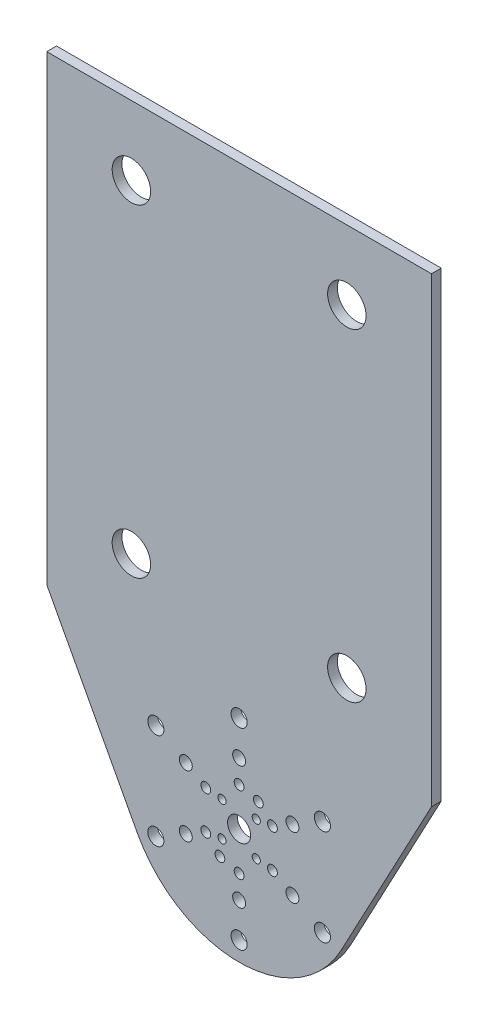
SolidWorks part; units mm, degrees
ref_plane "Front Plane" through (0, 0, 0) normal (0, 0, 1) x (1, 0, 0)
ref_plane "Top Plane" through (0, 0, 0) normal (0, 1, 0) x (1, 0, 0)
ref_plane "Right Plane" through (0, 0, 0) normal (1, 0, 0) x (0, 0, -1)
sketch "Sketch1" plane through (0, 0, 0) normal (0, 0, 1) x (1, 0, 0)
  line L0 (0, 375) -> (0, 0) construction
  line L1 (-125, 375) -> (125, 375)
  line L2 (-125, 375) -> (-125, 75)
  line L3 (-125, 75) -> (125, 75) construction
  line L4 (125, 375) -> (125, 75)
  line L5 (-66.1765, -35.2941) -> (-125, 75)
  line L6 (66.1765, -35.2941) -> (125, 75)
  arc A0 (-66.1765, -35.2941) -> (66.1765, -35.2941) centre (0, 0) ccw
  circle A1 centre (0, 0) radius 75 construction
  dimension "D3" = 75
  dimension "D1" = 250
  dimension "D2" = 300
extrude "Boss-Extrude1" add sketch "Sketch1" along normal blind 6.35
hole_wizard "SIA20 (80mm x M8 x 6)" positions "Sketch3" profile "Sketch2" hole size "M8" standard "ANSI Metric" end condition through all
sketch "Sketch3" plane through (0, 0, 6.35) normal (0, 0, 1) x (1, 0, 0)
  line L0 (0, 40) -> (0, -40) construction
  line L1 (-34.641, -20) -> (34.641, 20) construction
  line L2 (-34.641, 20) -> (34.641, -20) construction
  circle A0 centre (0, 0) radius 40 construction
  point P0 (-34.641, 20)
  point P14 (-34.641, -20)
  point P16 (0, -40)
  point P18 (34.641, -20)
  point P20 (34.641, 20)
  point P22 (0, 40)
  dimension "D1" = 80
  dimension "D2" = 60
  dimension "D3" = 60
sketch "Sketch2" plane through (-34.641, 20, 6.35) normal (1, 0, 0) x (0, -1, 0)
  line L0 (0, 0) -> (0, 6.35)
  line L1 (0, 6.35) -> (4.2, 6.35)
  line L2 (4.2, 6.35) -> (4.2, 0)
  line L5 (4.2, 0) -> (0, 0)
  line L11 (0, -6.35) -> (0, 107.95) construction
  dimension "Thru Hole Dia." = 8.4
  dimension "Thru Hole Depth" = 6.35
hole_wizard "IRB2400 (50mm x M6 x 6)" positions "Sketch7" profile "Sketch6" hole size "M6" standard "ANSI Metric" end condition through all
sketch "Sketch7" plane through (0, 0, 6.35) normal (0, 0, 1) x (1, 0, 0)
  line L0 (-34.641, 20) -> (34.641, -20) construction
  line L1 (-34.641, -20) -> (34.641, 20) construction
  circle A0 centre (0, 0) radius 25 construction
  point P6 (0, 25)
  point P8 (21.6506, -12.5)
  point P10 (21.6506, 12.5)
  point P14 (-21.6506, 12.5)
  point P16 (-21.6506, -12.5)
  point P18 (0, -25)
  dimension "D1" = 50
sketch "Sketch6" plane through (0, 25, 6.35) normal (1, 0, 0) x (0, -1, 0)
  line L0 (0, 0) -> (0, 6.35)
  line L1 (0, 6.35) -> (3.2, 6.35)
  line L2 (3.2, 6.35) -> (3.2, 0)
  line L5 (3.2, 0) -> (0, 0)
  line L11 (0, -6.35) -> (0, 107.95) construction
  dimension "Thru Hole Dia." = 6.4
  dimension "Thru Hole Depth" = 6.35
hole_wizard "UR5 (50mm x M6 x 4)" positions "Sketch9" profile "Sketch8" hole size "M6" standard "ANSI Metric" end condition through all
sketch "Sketch9" plane through (0, 0, 6.35) normal (0, 0, 1) x (1, 0, 0)
  line L0 (0, 40) -> (0, -40) construction
  line L2 (12.5, 21.6506) -> (21.6506, -12.5) construction
  line L3 (12.5, 21.6506) -> (-21.6506, 12.5) construction
  line L4 (-21.6506, 12.5) -> (-12.5, -21.6506) construction
  line L5 (21.6506, -12.5) -> (-12.5, -21.6506) construction
  circle A0 centre (0, 0) radius 25 construction
  point P0 (12.5, 21.6506)
  point P190 (-21.6506, 12.5)
  point P192 (-12.5, -21.6506)
  point P194 (21.6506, -12.5)
  dimension "D1" = 50
  dimension "D2" = 75
sketch "Sketch8" plane through (12.5, 21.6506, 6.35) normal (1, 0, 0) x (0, -1, 0)
  line L0 (0, 0) -> (0, 6.35)
  line L1 (0, 6.35) -> (3.2, 6.35)
  line L2 (3.2, 6.35) -> (3.2, 0)
  line L5 (3.2, 0) -> (0, 0)
  line L11 (0, -6.35) -> (0, 107.95) construction
  dimension "Thru Hole Dia." = 6.4
  dimension "Thru Hole Depth" = 6.35
hole_wizard "R2000 (125mm x M10 x 6)" positions "Sketch11" profile "Sketch10" hole size "M10" standard "ANSI Metric" end condition through all
sketch "Sketch11" plane through (0, 0, 6.35) normal (0, 0, 1) x (1, 0, 0)
  line L0 (-34.641, 20) -> (34.641, -20) construction
  line L3 (-34.641, -20) -> (34.641, 20) construction
  circle A0 centre (0, 0) radius 62.5 construction
  point P0 (-54.1266, 31.25)
  point P6 (0, 62.5)
  point P8 (54.1266, 31.25)
  point P10 (54.1266, -31.25)
  point P12 (0, -62.5)
  point P14 (-54.1266, -31.25)
  dimension "D1" = 125
sketch "Sketch10" plane through (-54.1266, 31.25, 6.35) normal (1, 0, 0) x (0, -1, 0)
  line L0 (0, 0) -> (0, 6.35)
  line L1 (0, 6.35) -> (5.25, 6.35)
  line L2 (5.25, 6.35) -> (5.25, 0)
  line L5 (5.25, 0) -> (0, 0)
  line L11 (0, -6.35) -> (0, 107.95) construction
  dimension "Thru Hole Dia." = 10.5
  dimension "Thru Hole Depth" = 6.35
hole_wizard "M5 Clearance Hole1" positions "Sketch17" profile "Sketch16" hole size "M5" standard "ANSI Metric" end condition through all
sketch "Sketch17" plane through (0, 0, 6.35) normal (0, 0, 1) x (1, 0, 0)
  line L1 (-11.1369, 11.1369) -> (-11.1369, -11.1369) construction
  line L2 (-11.1369, -11.1369) -> (11.1369, -11.1369) construction
  line L3 (11.1369, -11.1369) -> (11.1369, 11.1369) construction
  line L4 (11.1369, 11.1369) -> (-11.1369, 11.1369) construction
  circle A0 centre (0, 0) radius 15.75 construction
  point P0 (-11.1369, 11.1369)
  point P10 (11.1369, 11.1369)
  point P12 (11.1369, -11.1369)
  point P14 (-11.1369, -11.1369)
  dimension "D1" = 31.5
sketch "Sketch16" plane through (-11.1369, 11.1369, 6.35) normal (1, 0, 0) x (0, -1, 0)
  line L0 (0, 0) -> (0, 6.35)
  line L1 (0, 6.35) -> (2.65, 6.35)
  line L2 (2.65, 6.35) -> (2.65, 0)
  line L5 (2.65, 0) -> (0, 0)
  line L11 (0, -6.35) -> (0, 107.95) construction
  dimension "Thru Hole Dia." = 5.3
  dimension "Thru Hole Depth" = 6.35
hole_wizard "Ø25.0 (25) Diameter Hole2" positions "Sketch13" profile "Sketch12" hole size "Ø25.0" standard "ANSI Metric" end condition through all
sketch "Sketch13" plane through (0, 0, 6.35) normal (0, 0, 1) x (1, 0, 0)
  line L0 (0, 75) -> (0, 375) construction
  line L1 (125, 375) -> (-125, 375) construction
  line L2 (-125, 75) -> (125, 75) construction
  line L3 (-70, 330) -> (-70, 120) construction
  line L4 (-70, 225) -> (0, 225) construction
  point P0 (-70, 330)
  point P9 (-70, 120)
  point P14 (70, 120)
  point P15 (70, 330)
  dimension "D1" = 70
  dimension "D2" = 210
sketch "Sketch12" plane through (-70, 330, 6.35) normal (1, 0, 0) x (0, -1, 0)
  line L0 (0, 0) -> (0, 6.35)
  line L1 (0, 6.35) -> (12.5, 6.35)
  line L2 (12.5, 6.35) -> (12.5, 0)
  line L5 (12.5, 0) -> (0, 0)
  line L11 (0, -6.35) -> (0, 107.95) construction
  dimension "Thru Hole Dia." = 25
  dimension "Thru Hole Depth" = 6.35
hole_wizard "Ø15.0 (15) Diameter Hole1" positions "Sketch15" profile "Sketch14" hole size "Ø15.0" standard "ANSI Metric" end condition through all
sketch "Sketch15" plane through (0, 0, 6.35) normal (0, 0, 1) x (1, 0, 0)
  point P0 (0, 0)
sketch "Sketch14" plane through (0, 0, 6.35) normal (1, 0, 0) x (0, -1, 0)
  line L0 (0, 0) -> (0, 6.35)
  line L1 (0, 6.35) -> (7.5, 6.35)
  line L2 (7.5, 6.35) -> (7.5, 0)
  line L5 (7.5, 0) -> (0, 0)
  line L11 (0, -6.35) -> (0, 107.95) construction
  dimension "Thru Hole Dia." = 15
  dimension "Thru Hole Depth" = 6.35
